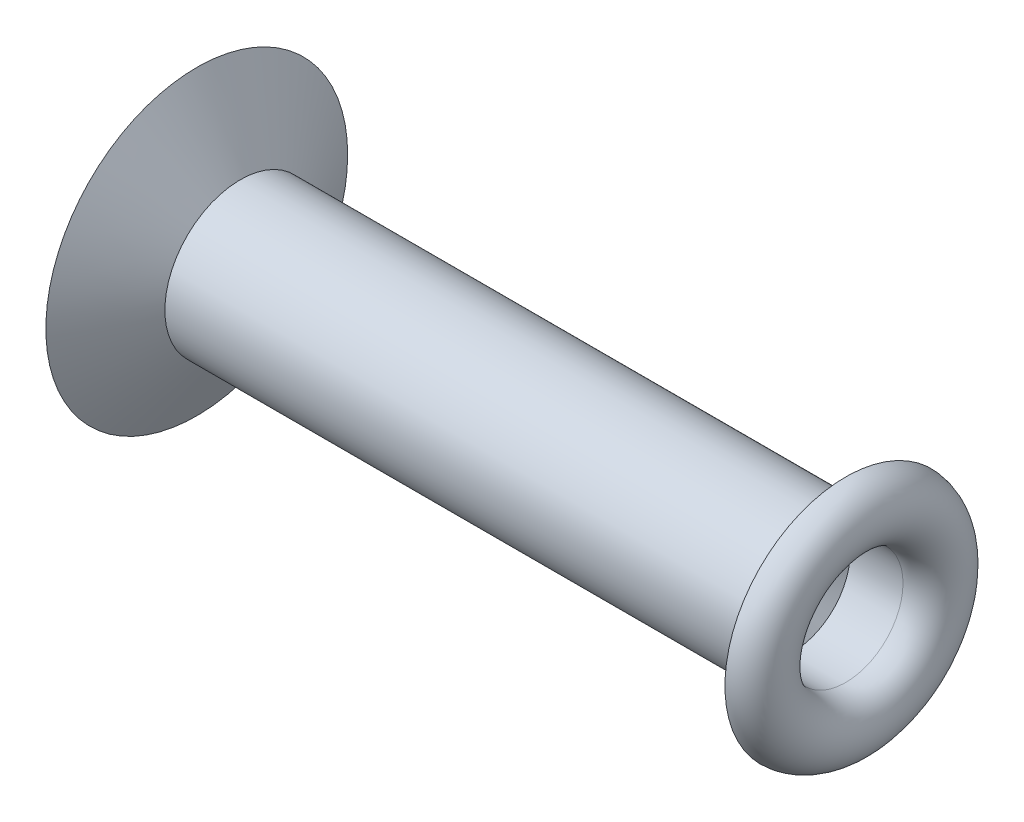
SolidWorks part; units mm, degrees
ref_plane "Plane1" through (0, 0, 0) normal (0, 0, 1) x (1, 0, 0)
ref_plane "Plane2" through (0, 0, 0) normal (0, 1, 0) x (1, 0, 0)
ref_plane "Plane3" through (0, 0, 0) normal (1, 0, 0) x (0, 0, -1)
sketch "Sketch1" plane through (0, 0, 0) normal (0, 0, 1) x (1, 0, 0)
  line L0 (40.3769, 0) -> (-46.1263, 0) construction
  line L1 (0, 8) -> (0, 6.7941)
  line L2 (-0.1025, 5) -> (-40.1132, 5)
  line L3 (-43, 0) -> (-43, 10)
  line L4 (-5.7833, 0) -> (-43, 0)
  line L5 (-43, 10) -> (-40.1132, 5)
  line L6 (0, 3.8) -> (-3.5, 3.8)
  line L7 (-3.5, 3.8) -> (-5.7833, 0)
  line L8 (-3.5, -3.8) -> (-5.7833, 0) construction
  line L9 (-0.1025, 5.9) -> (2, 5.9) construction
  line L10 (7, 0) -> (7, 21.0413) construction
  line L11 (-43, -10) -> (-40.1132, -5) construction
  arc A1 (0, 3.8) -> (0, 8) centre (-0.1025, 5.9) ccw
  arc A2 (-0.1025, 5) -> (0, 6.7941) centre (-0.1025, 5.9) ccw
  dimension "D1" = 118
  dimension "Diameter" = 10
  dimension "GripLength" = 43
  dimension "D2" = 120
  dimension "HeadDia" = 20
  dimension "HoleDepth" = 10.5
  dimension "HoleDia" = 7.6
  dimension "HeadKA" = 2
  dimension "HeadDiaA" = 16
  dimension "Length" = 50
revolve "Base-Revolve" add sketch "Sketch1" angle 360 about L0
